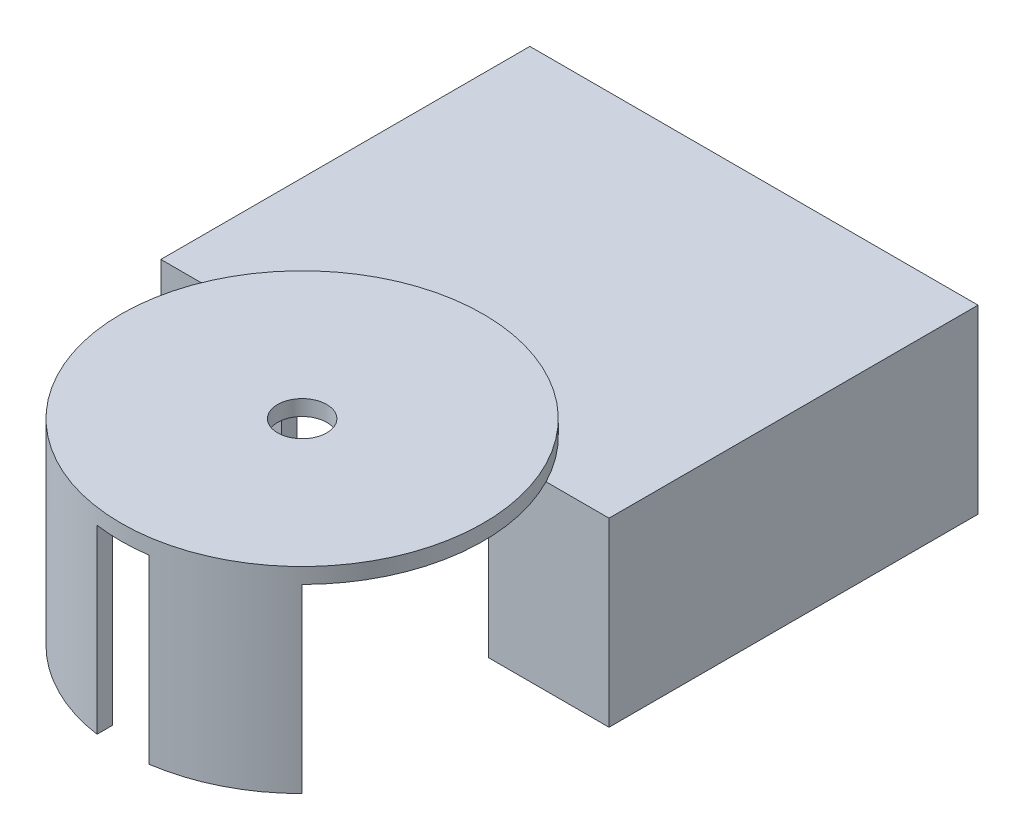
SolidWorks part; units mm, degrees
ref_plane "Alzado" through (0, 0, 0) normal (0, 0, 1) x (1, 0, 0)
ref_plane "Planta" through (0, 0, 0) normal (0, 1, 0) x (1, 0, 0)
ref_plane "Vista lateral" through (0, 0, 0) normal (1, 0, 0) x (0, 0, -1)
sketch "Croquis1" plane through (0, 0, 0) normal (0, 1, 0) x (1, 0, 0)
  circle A0 centre (0, 0) radius 4.75
  circle A1 centre (0, 0) radius 35
  dimension "D1" = 9.5
  dimension "D2" = 70
extrude "Saliente-Extruir1" add sketch "Croquis1" along normal blind 3
sketch "Croquis2" plane through (0, 0, 0) normal (0, -1, 0) x (1, 0, 0)
  circle A0 centre (-17.5, 8) radius 1.95
  circle A1 centre (17.5, 8) radius 1.95
  point P4 (0, 0)
  point P6 (0, 0)
  dimension "D4" = 3.9
  dimension "D1" = 8
  dimension "D2" = 35
  dimension "D3" = 17.5
extrude "Saliente-Extruir2" add sketch "Croquis2" along normal blind 5
sketch "Croquis5" plane through (0, 0, 0) normal (0, -1, 0) x (1, 0, 0)
  circle A0 centre (-17.5, 8) radius 2.25
  circle A1 centre (17.5, 8) radius 2.25
  dimension "D1" = 4.5
  dimension "D2" = 4.5
extrude "Saliente-Extruir3" add sketch "Croquis5" along normal up to surface (5 mm away) draft 4 from offset 1
sketch "Croquis3" plane through (0, -5, 0) normal (0, -1, 0) x (1, 0, 0)
  line L0 (-17.5, 9.95) -> (-17.5, 6.05) construction
  line L1 (-18, 11.0957) -> (-17, 11.0957)
  line L2 (-18, 11.0957) -> (-18, 4.255)
  line L3 (-18, 4.255) -> (-17, 4.255)
  line L4 (-17, 11.0957) -> (-17, 4.255)
  line L5 (17, 11.0957) -> (18, 11.0957)
  line L6 (17, 11.0957) -> (17, 4.255)
  line L7 (17, 4.255) -> (18, 4.255)
  line L8 (18, 11.0957) -> (18, 4.255)
  line L9 (17.5, 9.95) -> (17.5, 6.05) construction
  circle A0 centre (-17.5, 8) radius 1.95 construction
  circle A1 centre (-17.5, 8) radius 1.95 construction
  circle A2 centre (17.5, 8) radius 1.95 construction
  circle A3 centre (17.5, 8) radius 1.95 construction
  point P15 (-17.5, 11.0957)
  point P23 (17.5, 11.0957)
  dimension "D1" = 1
  dimension "D2" = 1
extrude "Cortar-Extruir1" cut sketch "Croquis3" against normal blind 4
sketch "Croquis6" plane through (0, -1, 0) normal (0, -1, 0) x (1, 0, 0)
  line L1 (-20.1225, 11.5076) -> (-14.3952, 11.5076)
  line L2 (-20.1225, 11.5076) -> (-20.1225, 9.8848)
  line L3 (-20.1225, 9.8848) -> (-14.3952, 9.8848)
  line L4 (-14.3952, 11.5076) -> (-14.3952, 9.8848)
  line L5 (-19.926, 5.5683) -> (-14.909, 5.5683)
  line L6 (-19.926, 5.5683) -> (-19.926, 6.1152)
  line L7 (-19.926, 6.1152) -> (-14.909, 6.1152)
  line L8 (-14.909, 5.5683) -> (-14.909, 6.1152)
  line L9 (19.9667, 11.0642) -> (15.2983, 11.0642)
  line L10 (19.9667, 11.0642) -> (19.9667, 9.8848)
  line L11 (19.9667, 9.8848) -> (15.2983, 9.8848)
  line L12 (15.2983, 11.0642) -> (15.2983, 9.8848)
  line L13 (19.6053, 4.5934) -> (15.0163, 4.5934)
  line L14 (19.6053, 4.5934) -> (19.6053, 6.1152)
  line L15 (19.6053, 6.1152) -> (15.0163, 6.1152)
  line L16 (15.0163, 4.5934) -> (15.0163, 6.1152)
  point P21 (0, 0)
extrude "Cortar-Extruir2" cut sketch "Croquis6" along normal up to surface (4 mm away)
sketch "Croquis7" plane through (0, 0, 0) normal (0, -1, 0) x (1, 0, 0)
  line L0 (-22.6512, 22.6512) -> (-24.7487, 24.7487)
  line L1 (0, 29.9917) -> (0, 35) construction
  line L2 (22.6512, 22.6512) -> (24.7487, 24.7487)
  line L5 (4.9999, 34.641) -> (4.9999, 31.641)
  line L9 (-4.9981, 34.6413) -> (-4.9981, 31.6413)
  arc A3 (-4.9981, 31.6413) -> (-22.6512, 22.6512) centre (0, 0) ccw
  arc A4 (-4.9981, 34.6413) -> (-24.7487, 24.7487) centre (0, 0) ccw
  arc A5 (22.6512, 22.6512) -> (4.9999, 31.641) centre (0, 0) ccw
  arc A6 (24.7487, 24.7487) -> (4.9999, 34.641) centre (0, 0) ccw
  circle A8 centre (0, 0) radius 35 construction
  dimension "D1" = 3
  dimension "D5" = 4.9981
  dimension "D6" = 4.9999
  dimension "D4" = 3
extrude "Saliente-Extruir4" add sketch "Croquis7" along normal blind 35
sketch "Croquis8" plane through (0, 0, 0) normal (0, -1, 0) x (1, 0, 0)
  line L1 (-34.3, -25) -> (34.3, -25) construction
  line L2 (-34.3, -25) -> (-34.3, -78.3) construction
  line L3 (-34.3, -78.3) -> (34.3, -78.3) construction
  line L4 (34.3, -25) -> (34.3, -78.3) construction
  point P4 (0, -25)
  dimension "D1" = 68.6
  dimension "D2" = 53.3
  dimension "D3" = 25
sketch "Croquis9" plane through (0, 0, 0) normal (0, -1, 0) x (1, 0, 0)
  line L1 (-43.3, -16) -> (43.3, -16)
  line L2 (-43.3, -16) -> (-43.3, -87.3)
  line L3 (-43.3, -87.3) -> (43.3, -87.3)
  line L4 (43.3, -16) -> (43.3, -87.3)
  line L5 (-34.3, -25) -> (-34.3, -78.3) construction
  line L6 (34.3, -25) -> (34.3, -78.3) construction
  line L7 (-34.3, -78.3) -> (34.3, -78.3) construction
  dimension "D1" = 16
  dimension "D2" = 9
  dimension "D3" = 9
  dimension "D4" = 9
extrude "Saliente-Extruir5" add sketch "Croquis9" along normal blind 3
sketch "Croquis10" plane through (0, -3, 0) normal (0, -1, 0) x (1, 0, 0)
  line L1 (-43.3, -16) -> (43.3, -16)
  line L2 (-43.3, -16) -> (-43.3, -87.3)
  line L3 (-43.3, -87.3) -> (43.3, -87.3)
  line L4 (43.3, -16) -> (43.3, -87.3)
  line L5 (-40.3, -19) -> (40.3, -19)
  line L6 (-40.3, -19) -> (-40.3, -84.3)
  line L7 (-40.3, -84.3) -> (40.3, -84.3)
  line L8 (40.3, -19) -> (40.3, -84.3)
  dimension "D1" = 3
  dimension "D2" = 3
  dimension "D3" = 3
  dimension "D4" = 3
extrude "Saliente-Extruir6" add sketch "Croquis10" along normal up to surface (32 mm away) up to face at (-14.7274, -35, 29.1701)
sketch "Croquis11" plane through (0, -35, 0) normal (0, -1, 0) x (1, 0, 0)
  line L0 (31.1288, -16) -> (-31.1288, -16) construction
  line L1 (-20, -16) -> (20, -16)
  line L2 (-20, -16) -> (-20, -19)
  line L3 (-20, -19) -> (20, -19)
  line L4 (20, -16) -> (20, -19)
  line L5 (40.3, -19) -> (-40.3, -19) construction
  point P8 (0, -16)
  dimension "D1" = 40
extrude "Cortar-Extruir3" cut sketch "Croquis11" against normal up to surface (35 mm away) up to face at (0, 0, 4.75)
sketch "Croquis12" plane through (0, -3, 0) normal (0, -1, 0) x (1, 0, 0)
  line L4 (-34.3, -25) -> (34.3, -25) construction
  line L7 (34.3, -25) -> (34.3, -78.3) construction
  circle A0 centre (31.8, -42.7) radius 2.5
  circle A1 centre (31.8, -70.6) radius 2.5
  circle A2 centre (-19, -27.5) radius 2.5
  circle A3 centre (-20.1, -75.3) radius 2.5
  circle A4 centre (-19, -27.5) radius 1.59
  circle A5 centre (31.8, -42.7) radius 1.59
  circle A6 centre (-20.1, -75.3) radius 1.59
  circle A7 centre (31.8, -70.6) radius 1.59
  point P13 (30.21, -70.6)
  dimension "D8" = 5
  dimension "D9" = 5
  dimension "D10" = 5
  dimension "D11" = 5
  dimension "D12" = 3.18
  dimension "D2" = 27.9
  dimension "D3" = 51.9
  dimension "D4" = 2.5
  dimension "D5" = 50.8
  dimension "D6" = 15.2
  dimension "D7" = 2.5
  dimension "D14" = 4.7
extrude "Saliente-Extruir7" add sketch "Croquis12" along normal blind 5
sketch "Croquis13" plane through (-40.3, 0, 0) normal (1, 0, 0) x (0, 0, -1)
  line L0 (19, -3) -> (84.3, -3) construction
  line L1 (33.6, -8) -> (47.6, -8)
  line L2 (33.6, -8) -> (33.6, -22)
  line L3 (33.6, -22) -> (47.6, -22)
  line L4 (47.6, -8) -> (47.6, -22)
  line L5 (65.3, -8) -> (76.3, -8)
  line L6 (65.3, -8) -> (65.3, -19)
  line L7 (65.3, -19) -> (76.3, -19)
  line L8 (76.3, -8) -> (76.3, -19)
  point P10 (25, 0)
  point P12 (78.3, 0)
  dimension "D1" = 5
  dimension "D2" = 5
  dimension "D3" = 14
  dimension "D4" = 14
  dimension "D5" = 8.6
  dimension "D6" = 11
  dimension "D7" = 11
  dimension "D8" = 2
extrude "Cortar-Extruir4" cut sketch "Croquis13" against normal up to surface (3 mm away) up to face at (-43.3, -17.5, -51.65)
